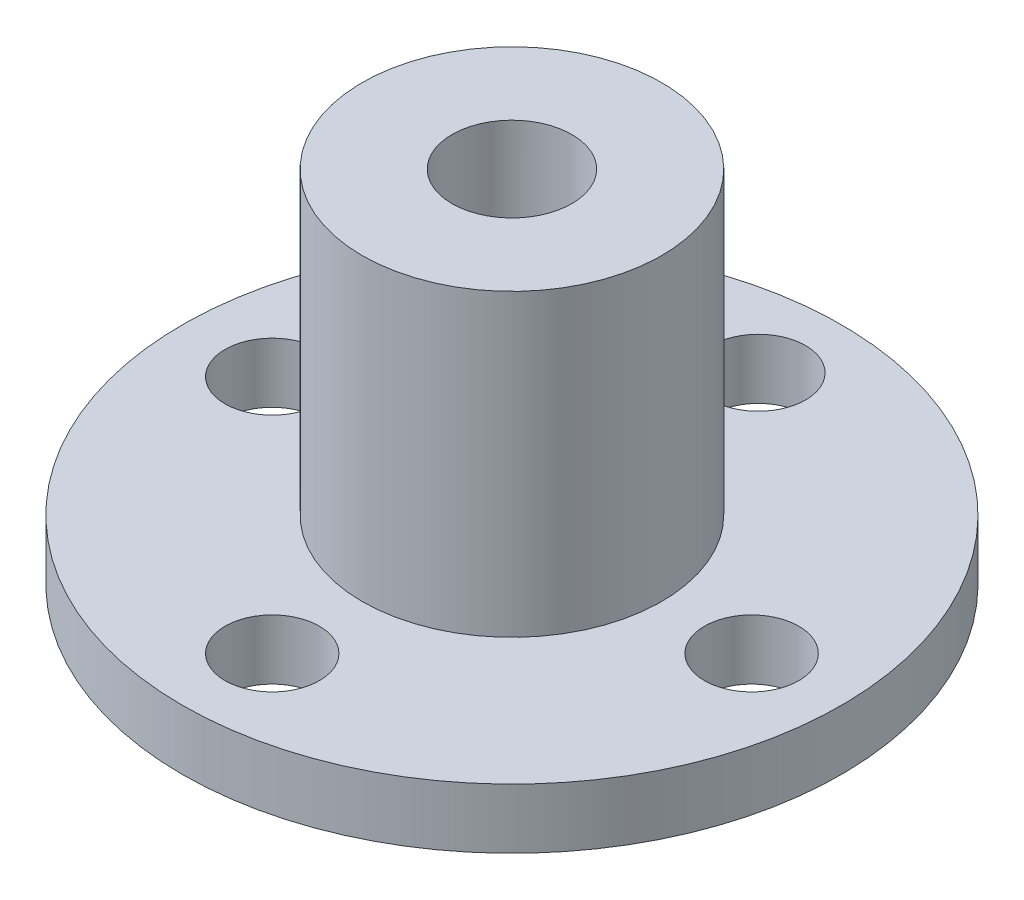
SolidWorks part; units mm, degrees
ref_plane "Спереди" through (0, 0, 0) normal (0, 0, 1) x (1, 0, 0)
ref_plane "Сверху" through (0, 0, 0) normal (0, 1, 0) x (1, 0, 0)
ref_plane "Справа" through (0, 0, 0) normal (1, 0, 0) x (0, 0, -1)
sketch "Эскиз2" plane through (0, 0, 0) normal (0, 1, 0) x (1, 0, 0)
  circle A0 centre (0, 0) radius 11
  dimension "D1" = 22
extrude "Бобышка-Вытянуть1" add sketch "Эскиз2" along normal blind 2
sketch "Эскиз7" plane through (0, 2, 0) normal (0, 1, 0) x (1, 0, 0)
  circle A0 centre (0, 0) radius 5
  dimension "D1" = 10
extrude "Бобышка-Вытянуть2" add sketch "Эскиз7" along normal blind 10
sketch "Эскиз8" plane through (0, 12, 0) normal (0, 1, 0) x (1, 0, 0)
  circle A0 centre (0, 0) radius 2
  dimension "D1" = 4
extrude "Вырез-Вытянуть3" cut sketch "Эскиз8" against normal up to next
sketch "Эскиз12" plane through (0, 0, 0) normal (0, 0, 1) x (1, 0, 0)
  line L0 (11, 2) -> (-11, 2) construction
  line L1 (5, 2) -> (5, 12) construction
  line L2 (-5, 12) -> (-5, 2) construction
  line L3 (5, 12) -> (-5, 12) construction
  line L4 (11, 2) -> (-11, 2) construction
  line L5 (5, 2) -> (5, 12) construction
  line L6 (-5, 12) -> (-5, 2) construction
  line L7 (5, 12) -> (-5, 12) construction
  line L8 (-5, 7) -> (5, 7) construction
  circle A0 centre (0, 7) radius 1.5
  dimension "D1" = 3
hole_wizard "Сверло под метчик  спиральное M31" positions "Эскиз18" profile "Эскиз19" hole size "M3x0.5" standard "DIN"
sketch "Эскиз18" plane through (0, 2, 0) normal (0, 1, 0) x (1, 0, 0)
  line L0 (-5, 0) -> (-11, 0) construction
  line L2 (0, 5) -> (0, 11) construction
  line L4 (5, 0) -> (11, 0) construction
  line L6 (0, -5) -> (0, -11) construction
  circle A0 centre (0, 0) radius 5 construction
  circle A1 centre (0, 0) radius 11 construction
  circle A2 centre (0, 0) radius 5 construction
  circle A3 centre (0, 0) radius 11 construction
  point P37 (-8, 0)
  point P39 (0, 8.2251)
  point P41 (8, 0)
  point P43 (0, -8)
sketch "Эскиз19" plane through (0, 2, 8) normal (1, 0, 0) x (0, 0, 1)
  line L0 (0, 0) -> (0, 8.9464)
  line L1 (0, 8.9464) -> (1.575, 8)
  line L2 (1.575, 8) -> (1.575, 0)
  line L5 (1.575, 0) -> (0, 0)
  line L10 (0, 8.9464) -> (-1.575, 8) construction
  line L11 (0, -6.35) -> (0, 107.95) construction
  dimension "Диаметр отверстия" = 3.15
  dimension "Глубина отверстия" = 8
  dimension "Угол заточки сверла" = 118
extrude "Вырез-Вытянуть4" cut sketch "Эскиз12" against normal blind 10 contours A0
